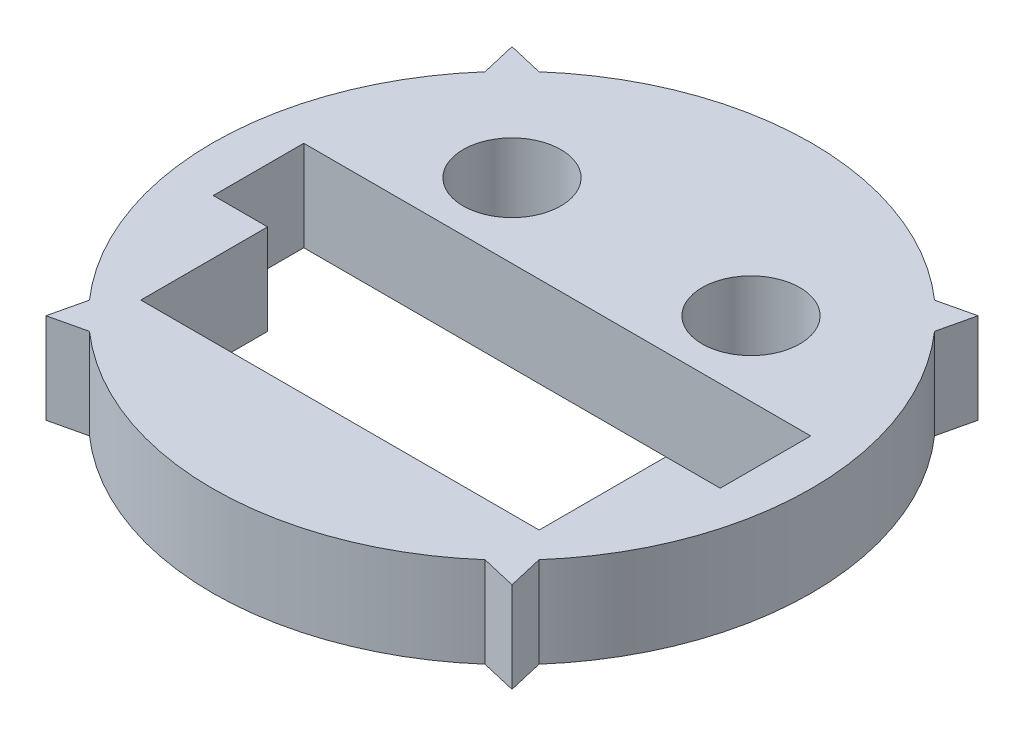
SolidWorks part; units mm, degrees
ref_plane "Front Plane" through (0, 0, 0) normal (0, 0, 1) x (1, 0, 0)
ref_plane "Top Plane" through (0, 0, 0) normal (0, 1, 0) x (1, 0, 0)
ref_plane "Right Plane" through (0, 0, 0) normal (1, 0, 0) x (0, 0, -1)
sketch "Sketch1" plane through (0, 0, 0) normal (0, 1, 0) x (1, 0, 0)
  line L0 (13.8701, 15.7677) -> (16.3439, 16.3439)
  line L1 (16.3439, 16.3439) -> (15.7677, 13.8701)
  line L2 (15.7677, -13.8701) -> (16.3439, -16.3439)
  line L3 (16.3439, -16.3439) -> (13.8701, -15.7677)
  line L4 (-13.8701, -15.7677) -> (-16.3439, -16.3439)
  line L5 (-16.3439, -16.3439) -> (-15.7677, -13.8701)
  line L6 (-15.7677, 13.8701) -> (-16.3439, 16.3439)
  line L7 (-16.3439, 16.3439) -> (-13.8701, 15.7677)
  line L8 (16.3439, 16.3439) -> (0, 0) construction
  line L9 (0, 0) -> (21, 0) construction
  line L10 (-20.7586, -3.175) -> (-13.97, -3.175) construction
  line L11 (13.97, -3.175) -> (20.7586, -3.175) construction
  line L13 (-13.97, -3.175) -> (-13.97, -12.065)
  line L14 (-13.97, -12.065) -> (13.97, -12.065)
  line L15 (13.97, -3.175) -> (13.97, -12.065)
  line L16 (-17.78, 3.175) -> (17.78, 3.175)
  line L17 (-17.78, 3.175) -> (-17.78, -3.175)
  line L18 (-17.78, -3.175) -> (-13.97, -3.175)
  line L19 (17.78, 3.175) -> (17.78, -3.175)
  line L20 (13.97, -3.175) -> (17.78, -3.175)
  arc A0 (13.8701, 15.7677) -> (-13.8701, 15.7677) centre (0, 0) ccw
  arc A1 (15.7677, -13.8701) -> (15.7677, 13.8701) centre (0, 0) ccw
  arc A2 (-13.8701, -15.7677) -> (13.8701, -15.7677) centre (0, 0) ccw
  arc A3 (-15.7677, 13.8701) -> (-15.7677, -13.8701) centre (0, 0) ccw
  circle A7 centre (-8.382, 8.382) radius 3.429
  circle A8 centre (8.382, 8.382) radius 3.429
  circle A9 centre (-12.7, 0) radius 2.8702 construction
  circle A10 centre (-6.35, 0) radius 2.8702 construction
  circle A11 centre (0, 0) radius 2.8702 construction
  circle A12 centre (6.35, 0) radius 2.8702 construction
  circle A13 centre (12.7, 0) radius 2.8702 construction
  point P18 (0, 0)
  point P28 (0, -12.065)
  point P41 (0, 3.175)
  dimension "D1" = 42
  dimension "D7" = 12.7
  dimension "D8" = 6.858
  dimension "D9" = 5.7404
  dimension "D2" = 2.54
  dimension "D3" = 2.54
  dimension "D5" = 23.1137
  dimension "D6" = 45
  dimension "D10" = 3.175
  dimension "D11" = 8.89
  dimension "D12" = 27.94
  dimension "D13" = 5
  dimension "D14" = 8.382
  dimension "D15" = 8.382
  dimension "D17" = 35.56
  dimension "D18" = 6.35
  dimension "D16" = 2
  dimension "D4" = 4
extrude "Boss-Extrude1" add sketch "Sketch1" along normal blind 6.35
